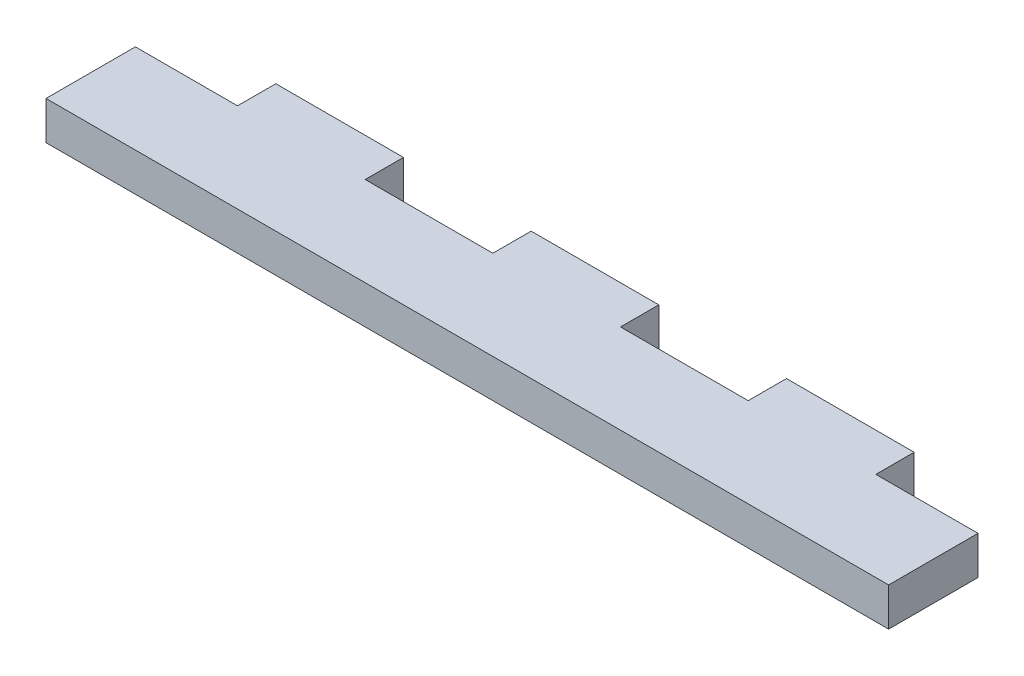
SolidWorks part; units mm, degrees
ref_plane "Front Plane" through (0, 0, 0) normal (0, 0, 1) x (1, 0, 0)
ref_plane "Top Plane" through (0, 0, 0) normal (0, 1, 0) x (1, 0, 0)
ref_plane "Right Plane" through (0, 0, 0) normal (1, 0, 0) x (0, 0, -1)
sketch "Sketch1" plane through (0, 0, 0) normal (0, 1, 0) x (1, 0, 0)
  line L1 (-33, 5) -> (33, 5)
  line L2 (-33, 5) -> (-33, -5)
  line L3 (-33, -5) -> (33, -5)
  line L4 (33, 5) -> (33, -5)
  line L5 (-33, 5) -> (33, -5) construction
  line L6 (-33, -5) -> (33, 5) construction
  point P0 (0, 0)
  dimension "D1" = 10
  dimension "D2" = 66
extrude "Boss-Extrude1" add sketch "Sketch1" along normal blind 3
sketch "Sketch2" plane through (0, 3, 0) normal (0, 1, 0) x (1, 0, 0)
  line L0 (0, 5) -> (0, -5) construction
  line L1 (33, 5) -> (-33, 5) construction
  line L2 (-33, -5) -> (33, -5) construction
  line L3 (-33, 0) -> (33, 0) construction
  line L4 (-33, 5) -> (-33, -5) construction
  line L5 (33, -5) -> (33, 5) construction
  line L6 (5, 5) -> (5, 2)
  line L7 (-33, 5) -> (-25, 5)
  line L8 (-33, 5) -> (-33, 2)
  line L9 (-33, 2) -> (-25, 2)
  line L10 (-25, 5) -> (-25, 2)
  line L11 (-15, 5) -> (-5, 5)
  line L12 (-15, 5) -> (-15, 2)
  line L13 (-15, 2) -> (-5, 2)
  line L14 (-5, 5) -> (-5, 2)
  line L15 (15, 2) -> (5, 2)
  line L16 (15, 5) -> (15, 2)
  line L17 (15, 5) -> (5, 5)
  line L18 (25, 5) -> (25, 2)
  line L19 (33, 2) -> (25, 2)
  line L20 (33, 5) -> (33, 2)
  line L21 (33, 5) -> (25, 5)
  dimension "D1" = 3
  dimension "D2" = 8
  dimension "D3" = 10
  dimension "D4" = 10
extrude "Cut-Extrude1" cut sketch "Sketch2" against normal blind 3
